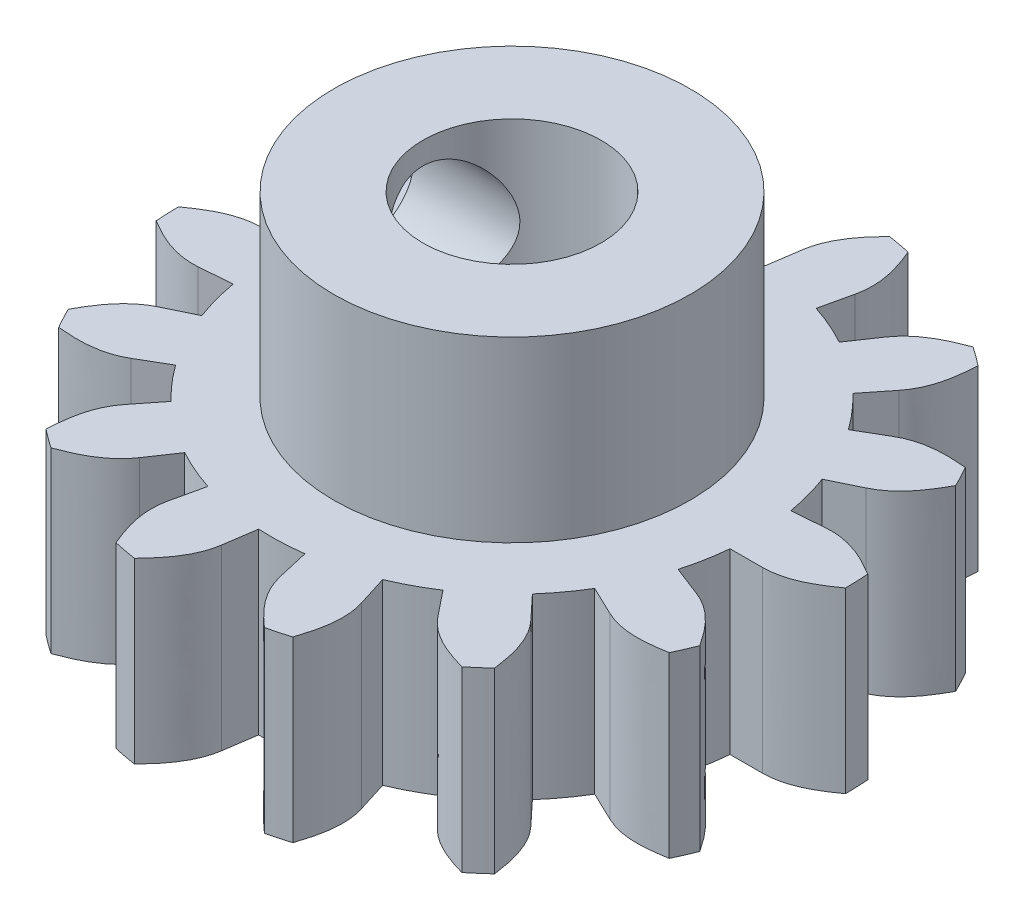
SolidWorks part; units mm, degrees
ref_plane "Front Plane" through (0, 0, 0) normal (0, 0, 1) x (1, 0, 0)
ref_plane "Top Plane" through (0, 0, 0) normal (0, 1, 0) x (1, 0, 0)
ref_plane "Right Plane" through (0, 0, 0) normal (1, 0, 0) x (0, 0, -1)
sketch "Sketch1" plane through (0, 0, 0) normal (0, 1, 0) x (1, 0, 0)
  line L0 (-7.9456, -0.0347) -> (8.3877, 0) construction
  line L1 (-8.169, -0.0304) -> (8.161, -0.0304) construction
  dimension "D1" = 16.3333
  dimension "D2" = 16.33
sketch "Sketch2" plane through (0, 0, 0) normal (0, 1, 0) x (1, 0, 0)
  line L1 (9.4591, 0.3802) -> (0, 0) construction
  line L2 (6.6652, 1.158) -> (7.5784, 1.23)
  line L3 (6.7366, -0.6194) -> (7.6527, -0.6178)
  circle A0 centre (0, 0) radius 8.15 construction
  arc A1 (6.7366, -0.6194) -> (6.6652, 1.158) centre (0, 0) ccw
  arc A2 (9.309, 0.0478) -> (9.2828, 0.6995) centre (0, 0) ccw
  arc A3 (9.2828, 0.6995) -> (9.309, 0.0478) centre (0, 0) ccw construction
  arc A4 (6.6652, 1.158) -> (6.7366, -0.6194) centre (0, 0) ccw construction
  spline S0 degree 3 poles (7.5784, 1.23) (8.2099, 1.2798) (8.7703, 1.0095) (9.2828, 0.6995) knots 0 0 0 0 1 1 1 1
  spline S1 degree 3 poles (7.6527, -0.6178) (8.2861, -0.6167) (8.823, -0.3024) (9.309, 0.0478) knots 0 0 0 0 1 1 1 1
  dimension "D1" = 16.3
extrude "Boss-Extrude1" add sketch "Sketch2" along normal blind 5
sketch "Sketch3" plane through (0, 0, 0) normal (0, 1, 0) x (1, 0, 0)
  arc A0 (6.6652, 1.158) -> (6.7366, -0.6194) centre (0, 0) ccw construction
  arc A1 (6.6652, 1.158) -> (6.7366, -0.6194) centre (0, 0) ccw
  circle A2 centre (0, 0) radius 6.765
extrude "Boss-Extrude2" add sketch "Sketch3" along normal blind 5 contours A1 A2
pattern_circular "CirPattern1" count 14 over 360 about axis through (0, 5, 0) along (0, -1, 0) of "Boss-Extrude1"
sketch "Sketch4" plane through (0, 5, 0) normal (0, 1, 0) x (1, 0, 0)
  circle A0 centre (0, 0) radius 2.5
  dimension "D1" = 5
extrude "Cut-Extrude1" cut sketch "Sketch4" against normal blind 10
sketch "Sketch5" plane through (0, 5, 0) normal (0, 1, 0) x (1, 0, 0)
  circle A0 centre (0, 0) radius 5
  circle A1 centre (0, 0) radius 2.5
  dimension "D1" = 10
  dimension "D2" = 5
extrude "Boss-Extrude3" add sketch "Sketch5" along normal blind 5
sketch "Sketch6" plane through (0, 0, 0) normal (1, 0, 0) x (0, 0, -1)
  line L0 (5, 5) -> (-5, 5) construction
  circle A0 centre (0, 7.5) radius 1.875
  dimension "D1" = 3.75
  dimension "D2" = 2.5
extrude "Cut-Extrude2" cut sketch "Sketch6" against normal blind 5
